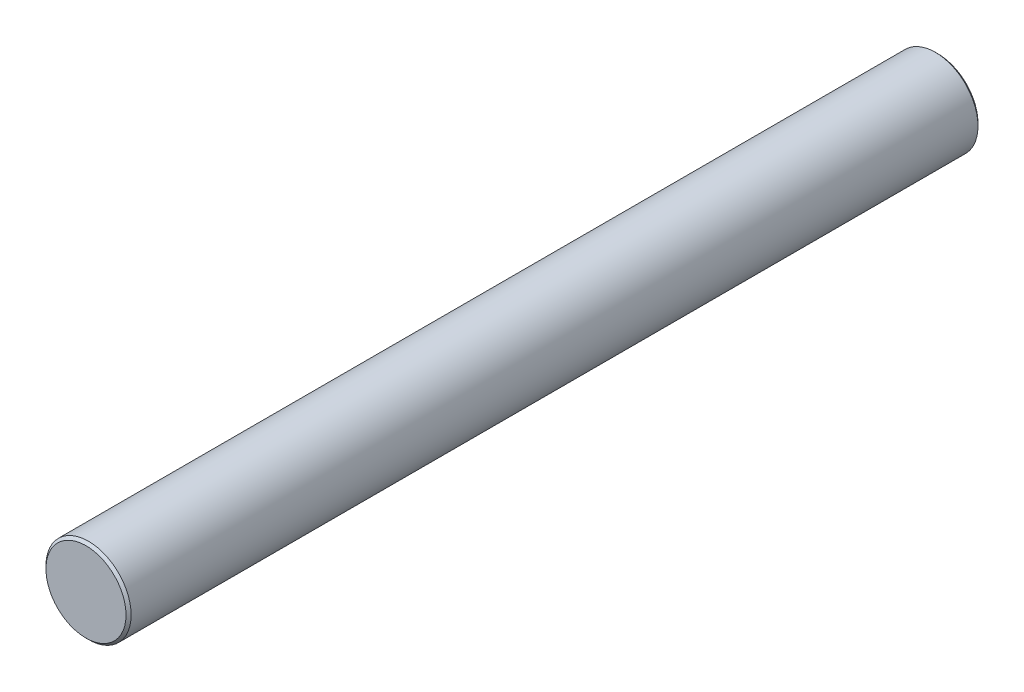
SolidWorks part; units mm, degrees
ref_plane "Front" through (0, 0, 0) normal (0, 0, 1) x (1, 0, 0)
ref_plane "Top" through (0, 0, 0) normal (0, 1, 0) x (1, 0, 0)
ref_plane "Right" through (0, 0, 0) normal (1, 0, 0) x (0, 0, -1)
sketch "Sketch1" plane through (0, 0, 0) normal (0, 0, 1) x (1, 0, 0)
  circle A0 centre (0, 0) radius 5
  dimension "D1" = 10
extrude "Boss-Extrude1" add sketch "Sketch1" along normal mid plane 100
chamfer "Chamfer1" distance 0.3 angle 45 2 edges at (5, 0, -50) (5, 0, 50)
